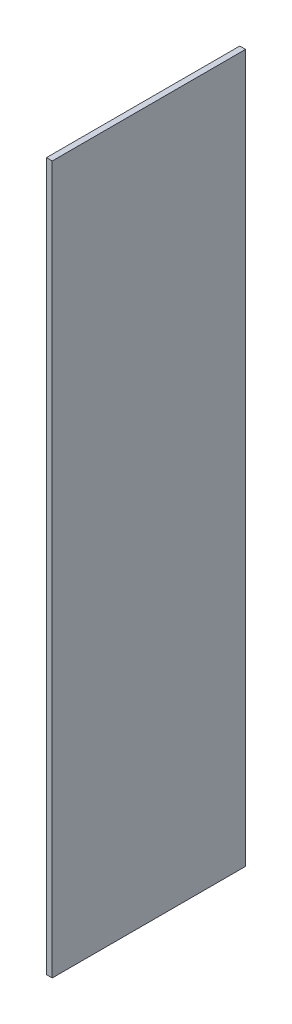
SolidWorks part; units mm, degrees
ref_plane "Front Plane" through (0, 0, 0) normal (0, 0, 1) x (1, 0, 0)
ref_plane "Top Plane" through (0, 0, 0) normal (0, 1, 0) x (1, 0, 0)
ref_plane "Right Plane" through (0, 0, 0) normal (1, 0, 0) x (0, 0, -1)
sketch "Sketch1" plane through (0, 0, 0) normal (1, 0, 0) x (0, 0, -1)
  line L1 (0, 0) -> (500, 0)
  line L2 (0, 0) -> (0, 1830)
  line L3 (0, 1830) -> (500, 1830)
  line L4 (500, 0) -> (500, 1830)
  dimension "D1" = 1830
  dimension "D2" = 500
extrude "Boss-Extrude1" add sketch "Sketch1" along normal blind 15
